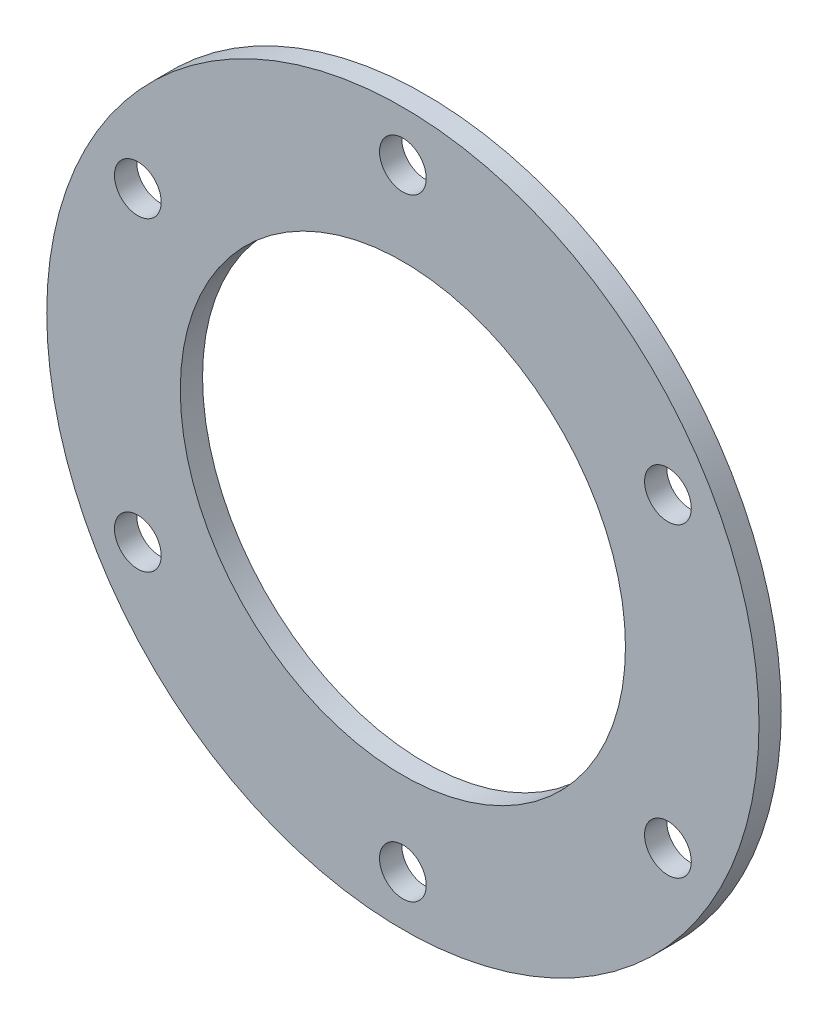
SolidWorks part; units mm, degrees
material "1.7033 (34Cr4)"
ref_plane "Спереди" through (0, 0, 0) normal (0, 0, 1) x (1, 0, 0)
ref_plane "Сверху" through (0, 0, 0) normal (0, 1, 0) x (1, 0, 0)
ref_plane "Справа" through (0, 0, 0) normal (1, 0, 0) x (0, 0, -1)
sketch "Эскиз1" plane through (0, 0, 0) normal (0, 0, 1) x (1, 0, 0)
  circle A0 centre (0, 0) radius 32
  circle A1 centre (0, 0) radius 20
  point P19 (0, 0)
  dimension "D1" = 64
  dimension "D2" = 40
extrude "Бобышка-Вытянуть1" add sketch "Эскиз1" along normal blind 2
sketch "Эскиз4" plane through (0, 0, 2) normal (0, 0, 1) x (1, 0, 0)
  circle A0 centre (0, 0) radius 27.5 construction
  point P0 (0, 27.5)
  dimension "D1" = 55
hole_wizard "Сверло под метчик  спиральное M41" positions "Эскиз4" profile "Эскиз3" hole size "M4x0.7" standard "DIN" end condition through all
sketch "Эскиз3" plane through (0, 27.5, 2) normal (1, 0, 0) x (0, -1, 0)
  line L0 (0, 0) -> (0, 2)
  line L1 (0, 2) -> (2.1, 2)
  line L2 (2.1, 2) -> (2.1, 0)
  line L5 (2.1, 0) -> (0, 0)
  line L11 (0, -6.35) -> (0, 107.95) construction
  dimension "Диаметр сквозного отверстия" = 4.2
  dimension "Глубина сквозного отверстия" = 2
pattern_circular "Круговой массив1" count 6 over 360 about axis through (0, 0, 0) along (0, 0, 1) of "Сверло под метчик  спиральное M41"
